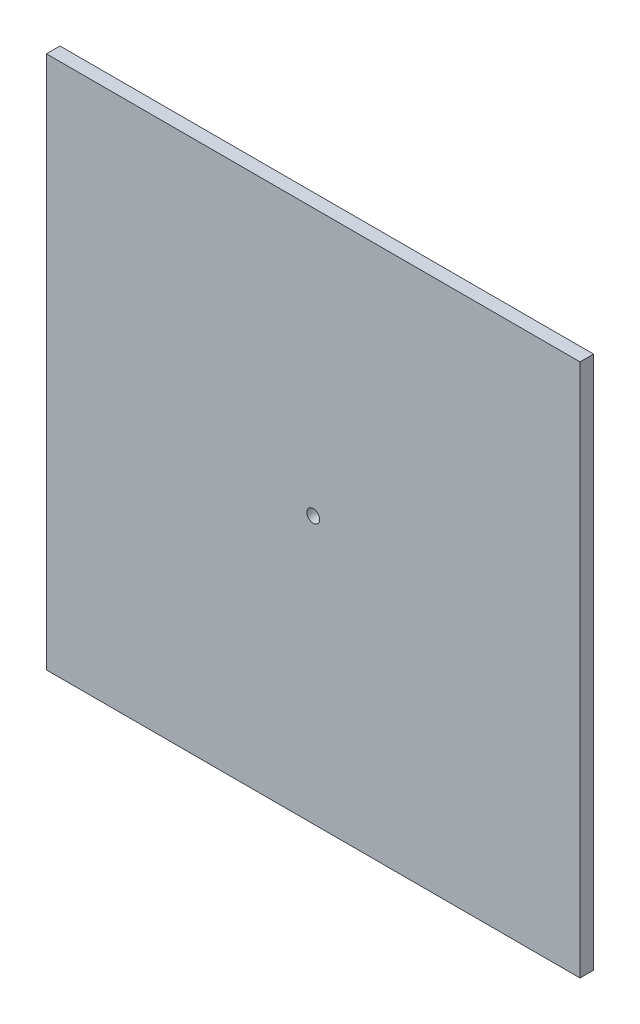
SolidWorks part; units mm, degrees
ref_plane "Alzado" through (0, 0, 0) normal (0, 0, 1) x (1, 0, 0)
ref_plane "Planta" through (0, 0, 0) normal (0, 1, 0) x (1, 0, 0)
ref_plane "Vista lateral" through (0, 0, 0) normal (1, 0, 0) x (0, 0, -1)
sketch "Sketch1" plane through (0, 0, 0) normal (0, 0, 1) x (1, 0, 0)
  line L1 (250, -250) -> (-250, -250)
  line L2 (250, -250) -> (250, 250)
  line L3 (250, 250) -> (-250, 250)
  line L4 (-250, -250) -> (-250, 250)
  line L5 (250, -250) -> (-250, 250) construction
  line L6 (250, 250) -> (-250, -250) construction
  point P0 (0, 0)
  dimension "D1" = 500
extrude "Boss-Extrude1" add sketch "Sketch1" along normal blind 12.7
sketch "Sketch4" plane through (0, 0, 12.7) normal (0, 0, 1) x (1, 0, 0)
  circle A0 centre (0, 0) radius 6
  dimension "D1" = 12
extrude "Cut-Extrude1" cut sketch "Sketch4" against normal up to surface (12.7 mm away) up to face at (0, 0, 0)
